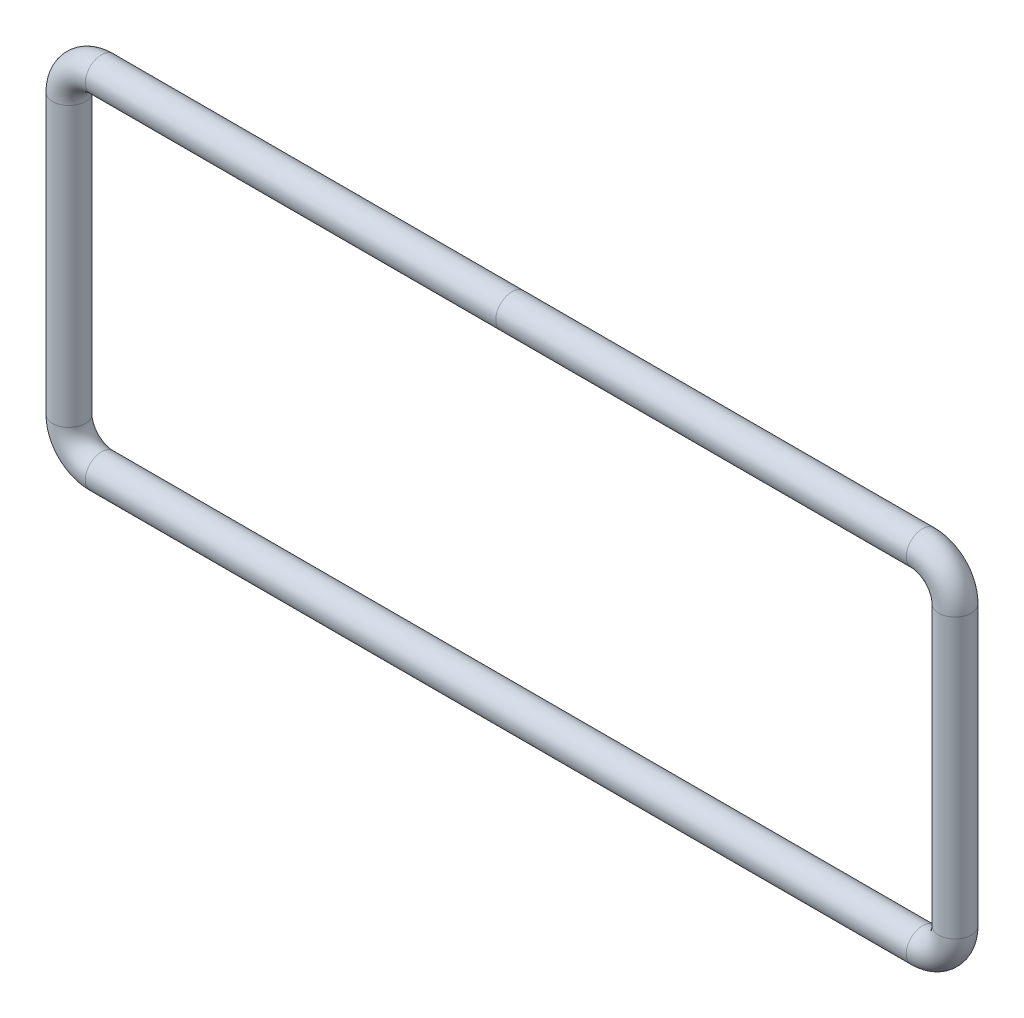
SolidWorks part; units mm, degrees
ref_plane "Plano frontal" through (0, 0, 0) normal (0, 0, 1) x (1, 0, 0)
ref_plane "Plano superior" through (0, 0, 0) normal (0, 1, 0) x (1, 0, 0)
ref_plane "Plano direito" through (0, 0, 0) normal (1, 0, 0) x (0, 0, -1)
sketch "Esboço1" plane through (0, 0, 0) normal (0, 0, 1) x (1, 0, 0)
  line L4 (53, 22.2) -> (-53, 22.2)
  line L5 (57.2, -18) -> (57.2, 18)
  line L6 (-53, -22.2) -> (53, -22.2)
  line L7 (-57.2, 18) -> (-57.2, -18)
  line L8 (53, 22.2) -> (-53, 22.2)
  line L9 (57.2, -18) -> (57.2, 18)
  line L10 (-53, -22.2) -> (53, -22.2)
  line L11 (-57.2, 18) -> (-57.2, -18)
  arc A4 (57.2, 18) -> (53, 22.2) centre (53, 18) ccw
  arc A5 (53, -22.2) -> (57.2, -18) centre (53, -18) ccw
  arc A6 (-57.2, -18) -> (-53, -22.2) centre (-53, -18) ccw
  arc A7 (-53, 22.2) -> (-57.2, 18) centre (-53, 18) ccw
  arc A8 (57.2, 18) -> (53, 22.2) centre (53, 18) ccw
  arc A9 (53, -22.2) -> (57.2, -18) centre (53, -18) ccw
  arc A10 (-57.2, -18) -> (-53, -22.2) centre (-53, -18) ccw
  arc A11 (-53, 22.2) -> (-57.2, 18) centre (-53, 18) ccw
  dimension "D1" = 0
sketch "Esboço2" plane through (0, 0, 0) normal (1, 0, 0) x (0, 0, -1)
  circle A0 centre (0, 22.2) radius 2.1
  point P0 (0, 22.2)
  dimension "D1" = 4.2
sweep "Varredura1" add profiles "Esboço2" path "Esboço1"
